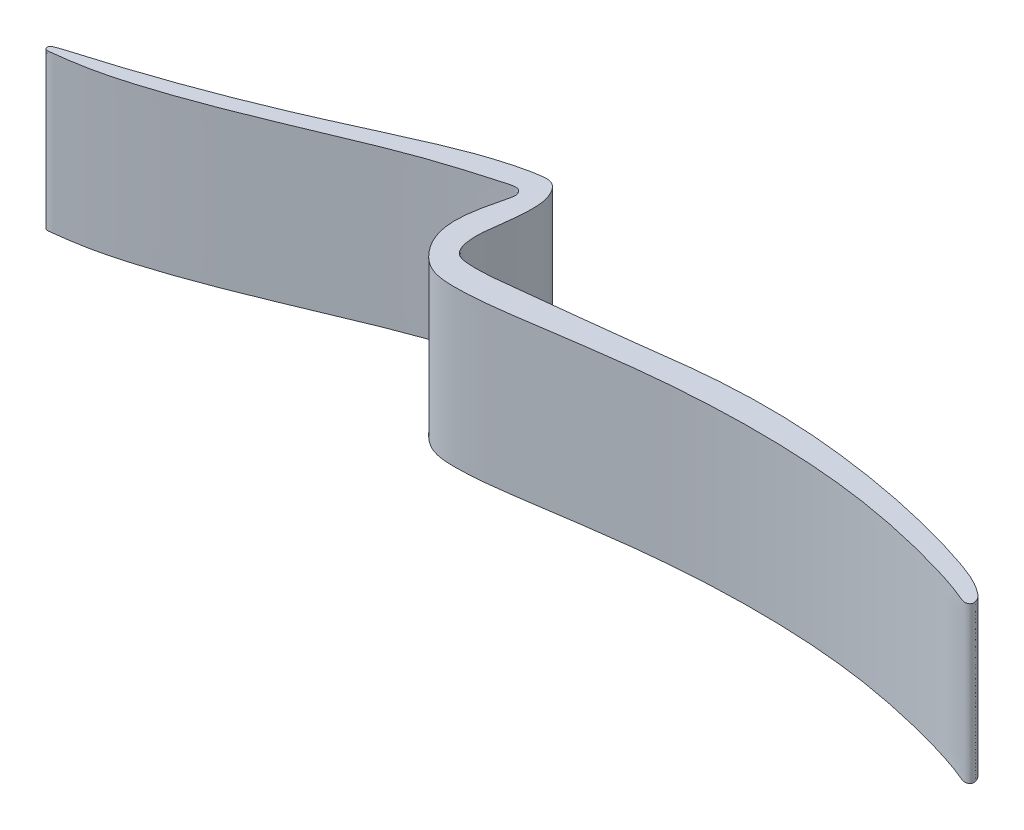
SolidWorks part; units mm, degrees
ref_plane "Front Plane" through (0, 0, 0) normal (0, 0, 1) x (1, 0, 0)
ref_plane "Top Plane" through (0, 0, 0) normal (0, 1, 0) x (1, 0, 0)
ref_plane "Right Plane" through (0, 0, 0) normal (1, 0, 0) x (0, 0, -1)
sketch "Sketch1" plane through (0, 0, 0) normal (0, 1, 0) x (1, 0, 0)
  line L0 (-29.4328, 22.585) -> (45.6579, 35.54) construction
  line L1 (1.2526, 44.1292) -> (77.4433, 42.9356) construction
  spline S0 degree 3 poles (1.0086, 44.6897) (2.8097, 45.2112) (8.0442, 46.8376) (15.0607, 49.5488) (21.2798, 52.479) (25.3143, 54.1843) (27.6442, 54.922) (29.4653, 55.3306) (30.7521, 55.4858) (31.7126, 54.242) (31.8408, 52.4462) (31.5738, 50.2025) (31.2894, 48.2921) (31.62, 46.9357) (32.0498, 46.4019) (32.6314, 46.2073) (34.3314, 46.0722) (36.6262, 46.4259) (40.1403, 46.7941) (44.6562, 47.2616) (50.6417, 48.1684) (57.6788, 48.3597) (65.4695, 47.4536) (71.9487, 45.9432) (76.2988, 44.3561) (77.4762, 43.3417) (77.7272, 42.6731) (77.1654, 42.4601) (76.2385, 42.8671) (74.2069, 43.5886) (70.3769, 44.6476) (64.9308, 45.7288) (56.9362, 46.3207) (48.0884, 45.8588) (40.121, 44.5598) (35.1036, 43.895) (32.1116, 44.0325) (30.4591, 45.4103) (29.3864, 47.3394) (29.4296, 49.9521) (29.9335, 51.7933) (30.2116, 53.0103) (29.8169, 53.6615) (27.3909, 52.9735) (23.3021, 51.7986) (16.8028, 49.019) (10.3963, 46.3784) (4.8636, 44.6302) (2.3012, 44.242) (0.5687, 44.0072) (0.5856, 44.4656) (1.0086, 44.6897) (2.8097, 45.2112) (8.0442, 46.8376) knots -0.007585 -0.006492 -0.005256 0 0.026347 0.087137 0.128901 0.143418 0.162035 0.170063 0.176071 0.182307 0.193936 0.206212 0.221045 0.226361 0.229572 0.232203 0.23655 0.258645 0.271451 0.296941 0.336089 0.374682 0.416795 0.469021 0.490138 0.492247 0.496601 0.498436 0.500952 0.513472 0.535617 0.568457 0.60819 0.672034 0.719364 0.745276 0.759552 0.767986 0.780839 0.795941 0.810901 0.814043 0.816634 0.822197 0.850447 0.896654 0.937992 0.97254 0.988235 0.992415 0.993508 0.994744 1 1.026347 1.087137 1.128901 only from (1.6545, 44.8778) to (1.6545, 44.8778)
  point P6 (0.6783, 44.4422)
  point P8 (0.8565, 44.5529)
  point P10 (30.0114, 53.4421)
  point P12 (24.1394, 51.9807)
  point P14 (28.9642, 53.4881)
  point P16 (30.7268, 45.357)
  point P18 (29.6771, 47.3045)
  point P20 (32.5905, 44.1632)
  point P22 (34.3278, 44.0152)
  point P24 (72.4845, 45.6179)
  point P26 (76.7455, 43.857)
  point P28 (77.2402, 43.4651)
  point P30 (76.8268, 42.6634)
  point P32 (73.8091, 45.1831)
  point P34 (64.8055, 47.322)
  point P36 (50.7012, 47.9476)
  point P38 (39.4518, 46.6158)
  point P40 (37.2232, 46.3861)
  point P42 (33.2027, 46.079)
  point P44 (32.3864, 46.2291)
  point P46 (32.0548, 46.4186)
  point P48 (31.6617, 46.8424)
  point P50 (31.4979, 50.4119)
  point P52 (28.2542, 54.9894)
  point P54 (29.6713, 55.2625)
  point P56 (25.1367, 54.0001)
  point P58 (22.9167, 53.0978)
  point P60 (16.1128, 50.035)
  point P62 (6.1768, 46.2336)
  point P64 (4.0321, 44.6136)
  point P66 (9.8024, 46.3217)
  point P68 (1.2768, 44.152)
  point P70 (77.3512, 42.5818)
  point P72 (0.7958, 44.5521)
  point P74 (0.6516, 44.452)
  point P76 (0.5961, 44.2431)
  point P78 (1.2799, 44.131)
  point P80 (4.0413, 44.5543)
  point P82 (9.8612, 46.2888)
  point P84 (16.6187, 48.9601)
  point P86 (24.1657, 51.9623)
  point P88 (28.9287, 53.4243)
  point P90 (29.9731, 53.4023)
  point P92 (30.1357, 53.0407)
  point P94 (29.8946, 53.4271)
  point P96 (28.917, 53.4061)
  point P98 (30.0914, 52.4902)
  point P100 (29.5372, 49.9195)
  point P102 (29.6328, 47.2667)
  point P104 (30.7382, 45.3079)
  point P105 (31.8874, 44.3713)
  point P106 (34.3663, 43.9808)
  point P107 (38.9004, 44.4144)
  point P108 (47.1389, 45.5731)
  point P109 (58.3488, 46.1033)
  point P110 (65.3107, 45.5449)
  point P111 (70.9769, 44.4417)
  point P112 (75.763, 43.0491)
  point P113 (76.8856, 42.6169)
  point P114 (74.537, 43.4591)
  point P115 (77.4389, 42.5672)
  point P116 (77.6071, 42.8818)
  point P117 (77.4701, 42.5422)
  point P118 (76.8782, 42.5999)
  point P119 (75.4983, 43.1252)
  point P120 (76.5285, 42.7149)
  point P121 (73.5838, 43.7497)
  point P122 (76.4647, 42.7605)
  point P123 (77.2168, 42.5144)
  point P124 (77.5267, 42.6329)
  point P125 (76.0818, 42.9018)
  point P126 (74.7234, 43.385)
  point P127 (76.7883, 42.6238)
  point P128 (77.5131, 42.642)
  point P129 (77.3034, 43.4534)
  point P130 (76.8202, 43.8591)
  point P131 (77.3718, 43.3941)
  point P132 (77.1074, 43.6539)
  point P133 (73.7516, 45.2405)
  point P134 (64.83, 47.4047)
  point P135 (57.4702, 48.1988)
  point P136 (50.6882, 48.0316)
  point P137 (43.8564, 47.2068)
  point P138 (39.4028, 46.7165)
  point P139 (37.1654, 46.4689)
  point P140 (33.2936, 46.1644)
  point P141 (32.5348, 46.2544)
  point P142 (32.1049, 46.4249)
  point P143 (31.7305, 46.8474)
  point P144 (31.4563, 47.7406)
  point P145 (31.581, 50.3451)
  point P146 (31.775, 52.4941)
  point P147 (31.4173, 54.5067)
  point P148 (30.6691, 55.3079)
  point P149 (29.6056, 55.295)
  point P150 (28.2328, 55.0414)
  point P151 (29.6133, 55.3336)
  point P152 (25.1108, 54.0601)
  point P153 (22.7504, 53.091)
  point P154 (16.0491, 50.0929)
  point P155 (6.0752, 46.2587)
  point P156 (2.866, 45.2269)
  point P157 (0.7632, 44.545)
  point P158 (0.6125, 44.4346)
  point P159 (0.7842, 44.5677)
  point P160 (1.6545, 44.8778)
  point P161 (1.3186, 44.1095)
  point P162 (30.7212, 45.2868)
  dimension "D1" = 76.2
  dimension "D2" = 76.2
extrude "Boss-Extrude1" add sketch "Sketch1" along normal blind 12.7
